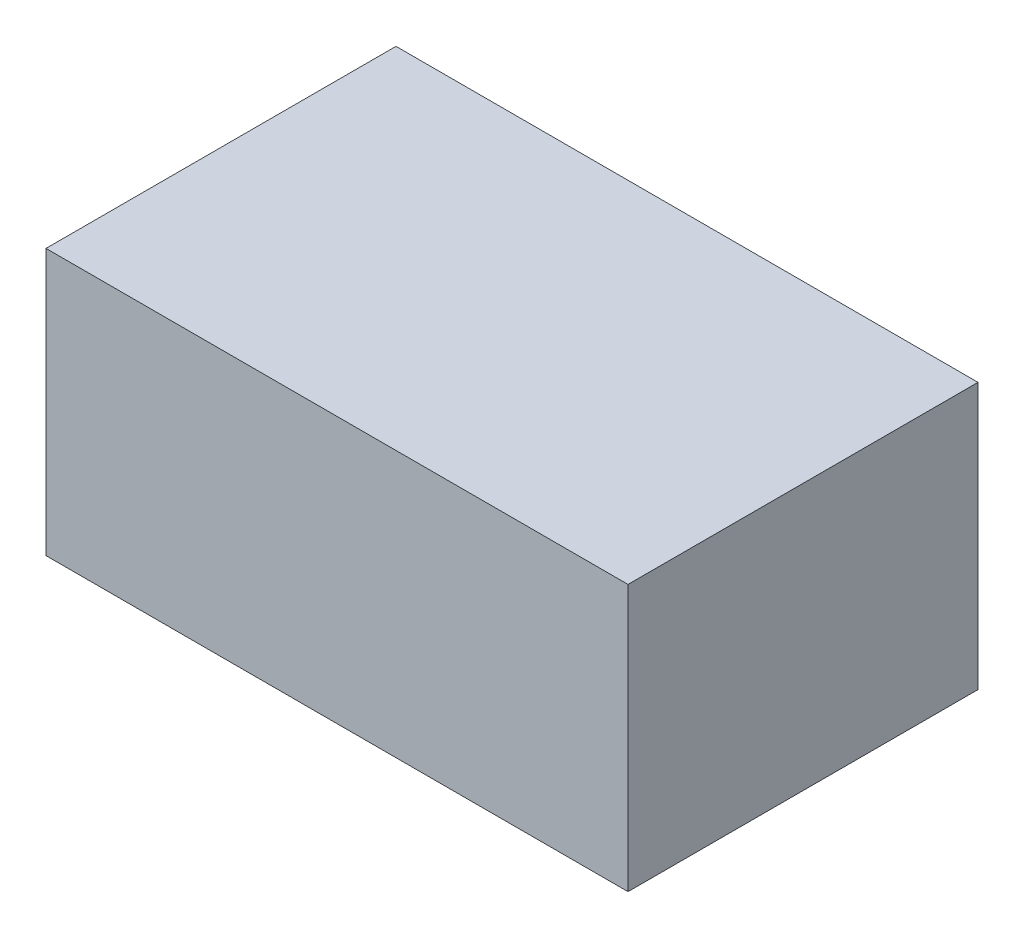
SolidWorks part; units mm, degrees
ref_plane "Front Plane" through (0, 0, 0) normal (0, 0, 1) x (1, 0, 0)
ref_plane "Top Plane" through (0, 0, 0) normal (0, 1, 0) x (1, 0, 0)
ref_plane "Right Plane" through (0, 0, 0) normal (1, 0, 0) x (0, 0, -1)
sketch "Sketch1" plane through (0, 0, 0) normal (0, 0, 1) x (1, 0, 0)
  line L1 (-22.2, -10.15) -> (22.2, -10.15)
  line L2 (-22.2, -10.15) -> (-22.2, 10.15)
  line L3 (-22.2, 10.15) -> (22.2, 10.15)
  line L4 (22.2, -10.15) -> (22.2, 10.15)
  line L5 (-22.2, -10.15) -> (22.2, 10.15) construction
  line L6 (-22.2, 10.15) -> (22.2, -10.15) construction
  point P0 (0, 0)
extrude "Envelope" add sketch "Sketch1" along normal blind 26.7
